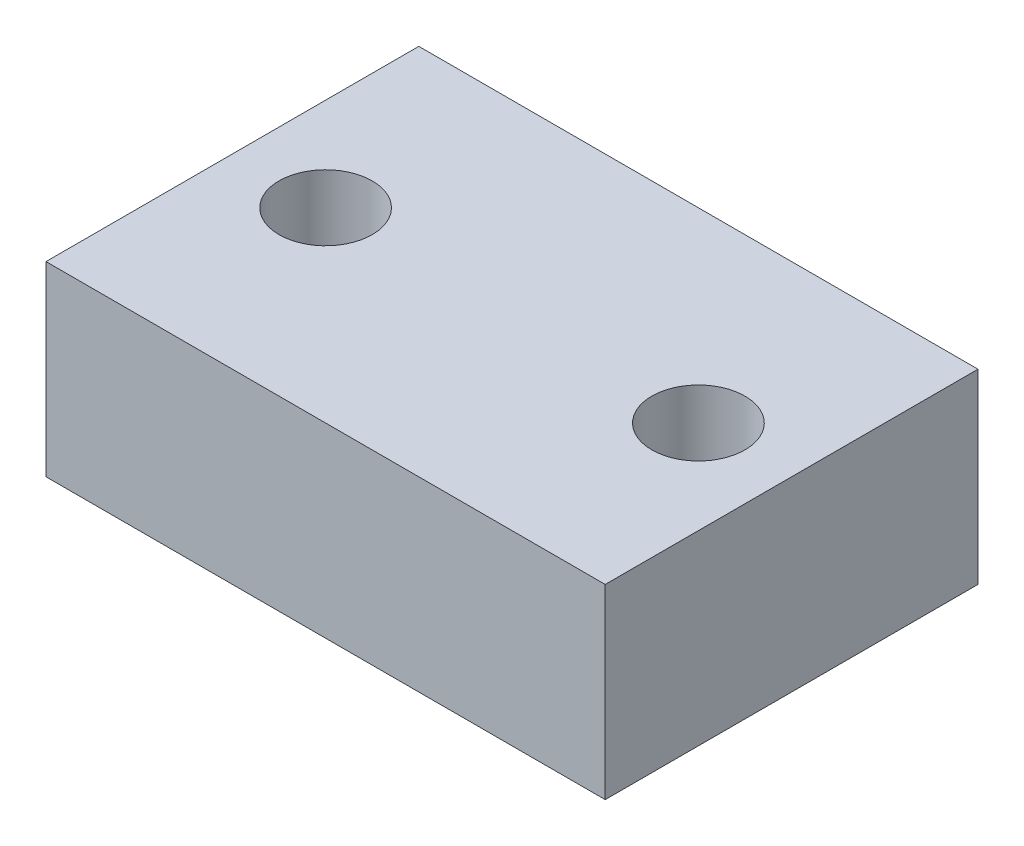
SolidWorks part; units mm, degrees
ref_plane "Front Plane" through (0, 0, 0) normal (0, 0, 1) x (1, 0, 0)
ref_plane "Top Plane" through (0, 0, 0) normal (0, 1, 0) x (1, 0, 0)
ref_plane "Right Plane" through (0, 0, 0) normal (1, 0, 0) x (0, 0, -1)
sketch "Sketch1" plane through (0, 0, 0) normal (0, 1, 0) x (1, 0, 0)
  line L0 (-30, -20) -> (30, -20)
  line L1 (30, -20) -> (30, 20)
  line L2 (30, 20) -> (-30, 20)
  line L3 (-30, 20) -> (-30, -20)
extrude "Boss-Extrude1" add sketch "Sketch1" along normal blind 20
sketch "Sketch2" plane through (0, 20, 0) normal (0, 1, 0) x (1, 0, 0)
  circle A0 centre (20, 0) radius 5
extrude "Cut-Extrude1" cut sketch "Sketch2" against normal through all
mirror "Mirror1" about plane through (0, 0, 0) normal (1, 0, 0) of "Cut-Extrude1"
